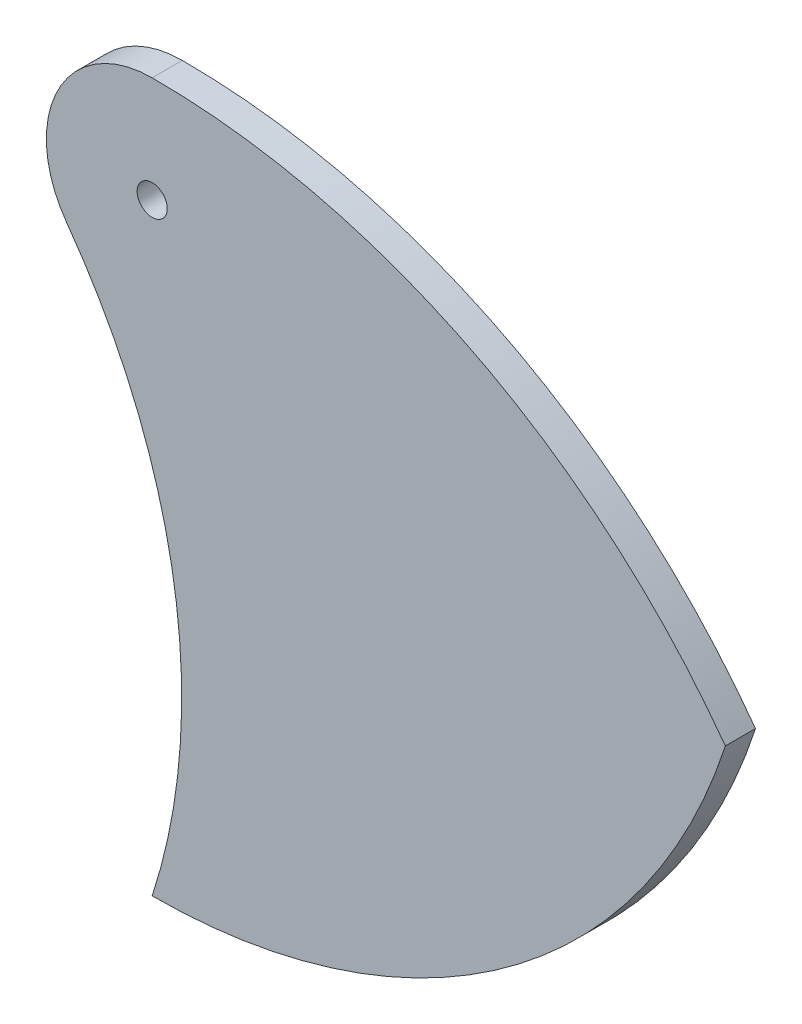
SolidWorks part; units mm, degrees
ref_plane "Front Plane" through (0, 0, 0) normal (0, 0, 1) x (1, 0, 0)
ref_plane "Top Plane" through (0, 0, 0) normal (0, 1, 0) x (1, 0, 0)
ref_plane "Right Plane" through (0, 0, 0) normal (1, 0, 0) x (0, 0, -1)
sketch "Sketch1" plane through (0, 0, 0) normal (0, 0, 1) x (1, 0, 0)
  circle A16 centre (0, 0) radius 25 construction
  circle A18 centre (0, 0) radius 30 construction
  circle A19 centre (0, 30) radius 0.75 construction
  circle A20 centre (0, 30) radius 5.2671 construction
  circle A21 centre (28.5317, 9.2705) radius 0.75 construction
  circle A22 centre (28.5317, 9.2705) radius 5.2671 construction
  circle A23 centre (17.6336, -24.2705) radius 0.75 construction
  circle A24 centre (17.6336, -24.2705) radius 5.2671 construction
  circle A25 centre (-17.6336, -24.2705) radius 0.75 construction
  circle A26 centre (-17.6336, -24.2705) radius 5.2671 construction
  circle A27 centre (-28.5317, 9.2705) radius 0.75 construction
  circle A28 centre (-28.5317, 9.2705) radius 5.2671 construction
  circle A29 centre (0, 30) radius 30 construction
  circle A34 centre (0, 0) radius 35.2671 construction
  arc A35 (0, 35.2671) -> (28.5317, 20.7295) centre (0, 0) cw
  arc A36 (0, 0) -> (28.5317, 20.7295) centre (0, 30) ccw
  arc A37 (0, 35.2671) -> (-4.2612, 26.9041) centre (0, 30) ccw
  arc A38 (-28.5317, -20.7295) -> (-16.9297, -18.3952) centre (-28.5317, 9.2705) ccw
  arc A39 (0, 0) -> (-4.2612, 26.9041) centre (-28.5317, 9.2705) ccw
  circle A40 centre (0, 30) radius 0.75
  point P21 (0, 0)
  point P31 (0, 0)
  dimension "D1" = 50
  dimension "D2" = 60
  dimension "D3" = 1.5
  dimension "D6" = 5
extrude "Boss-Extrude1" add sketch "Sketch1" along normal blind 1.5 contours A39 A36 A35 A37
